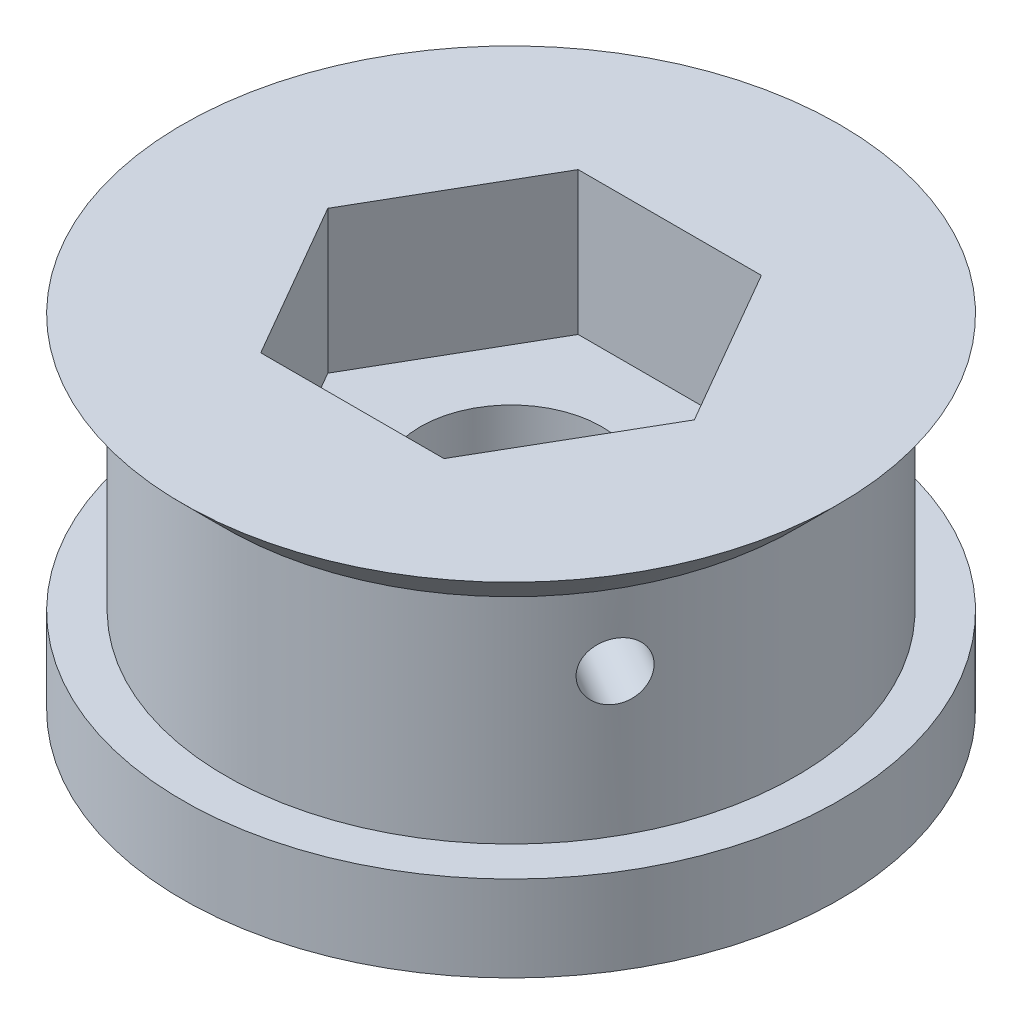
SolidWorks part; units mm, degrees
ref_plane "Front Plane" through (0, 0, 0) normal (0, 0, 1) x (1, 0, 0)
ref_plane "Top Plane" through (0, 0, 0) normal (0, 1, 0) x (1, 0, 0)
ref_plane "Right Plane" through (0, 0, 0) normal (1, 0, 0) x (0, 0, -1)
sketch "Sketch1" plane through (0, 0, 0) normal (0, 0, 1) x (1, 0, 0)
  line L0 (3.175, 0) -> (3.175, 12)
  line L3 (3.175, 12) -> (11.5, 12)
  line L4 (11.5, 12) -> (10, 10.5)
  line L5 (10, 10.5) -> (10, 3)
  line L6 (10, 3) -> (11.5, 3)
  line L7 (11.5, 3) -> (11.5, 0)
  line L8 (11.5, 0) -> (3.175, 0)
  line L9 (0, 0) -> (0, 12) construction
  dimension "D1" = 6.35
  dimension "D3" = 20
  dimension "D4" = 23
  dimension "D5" = 45
  dimension "D6" = 12
  dimension "D7" = 3
revolve "Revolve1" add sketch "Sketch1" angle 360 about L9
sketch "Sketch2" plane through (0, 12, 0) normal (0, 1, 0) x (1, 0, 0)
  line L1 (3.2079, 5.5563) -> (-3.2079, 5.5563)
  line L2 (-3.2079, 5.5563) -> (-6.4158, 0)
  line L3 (-6.4158, 0) -> (-3.2079, -5.5562)
  line L4 (-3.2079, -5.5562) -> (3.2079, -5.5562)
  line L5 (3.2079, -5.5562) -> (6.4158, 0)
  line L6 (6.4158, 0) -> (3.2079, 5.5563)
  circle A0 centre (0, 0) radius 5.5563 construction
  dimension "D1" = 11.1125
extrude "Cut-Extrude1" cut sketch "Sketch2" against normal blind 5
sketch "Sketch4" plane through (0, 0, -5.5563) normal (0, 0, 1) x (1, 0, 0)
  line L0 (-3.2079, 7) -> (3.2079, 12) construction
  circle A0 centre (0, 9.5) radius 1
  dimension "D1" = 2
extrude "Cut-Extrude2" [suppressed] cut sketch "Sketch4" against normal through all both and the other way through all
sketch "Sketch5" plane through (4.8119, 0, 2.7781) normal (-0.866, 0, -0.5) x (-0.5, 0, 0.866)
  line L4 (3.2079, 12) -> (-3.2079, 12)
  line L5 (-3.2079, 12) -> (-3.2079, 7)
  line L6 (-3.2079, 7) -> (3.2079, 7)
  line L7 (3.2079, 7) -> (3.2079, 12)
  line L10 (-3.2079, 7) -> (3.2079, 7) construction
  circle A0 centre (0, 8) radius 1
  dimension "D1" = 2
  dimension "D2" = 0
extrude "Cut-Extrude3" cut sketch "Sketch5" against normal through all
